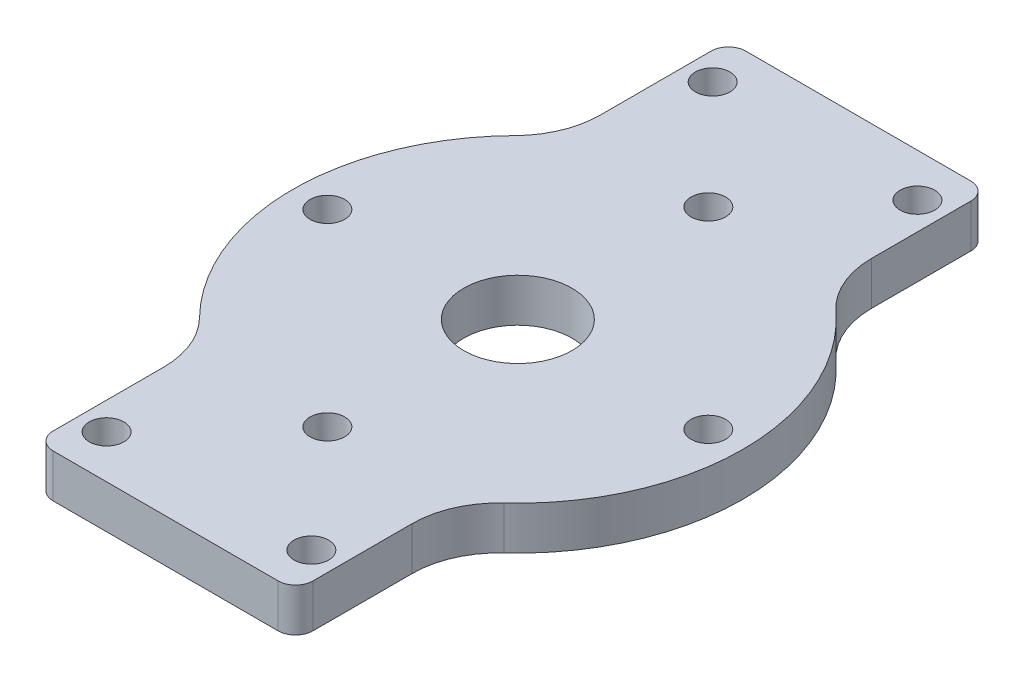
SolidWorks part; units mm, degrees
material "Hexcel AS4C (3000 Filaments)"
ref_plane "Ön Düzlem" through (0, 0, 0) normal (0, 0, 1) x (1, 0, 0)
ref_plane "Üst Düzlem" through (0, 0, 0) normal (0, 1, 0) x (1, 0, 0)
ref_plane "Sağ Düzlem" through (0, 0, 0) normal (1, 0, 0) x (0, 0, -1)
sketch "Çizim1" plane through (0, 0, 0) normal (0, 1, 0) x (1, 0, 0)
  line L0 (0, 40) -> (0, -40) construction
  line L1 (-15.6757, 40) -> (-15.6757, 25.2341)
  line L2 (14.3243, 40) -> (14.3243, 26.5392)
  line L3 (-15.6757, 40) -> (14.3243, 40)
  line L4 (-15.6757, -40) -> (14.3243, -40)
  line L5 (14.3243, -26.5392) -> (14.3243, -40)
  line L6 (14.3243, 40) -> (14.3243, -40) construction
  line L7 (-15.6757, -25.2341) -> (-15.6757, -40)
  line L8 (-15.6757, 40) -> (-15.6757, -40) construction
  arc A0 (-18.5435, 18.2246) -> (-18.5435, -18.2246) centre (0, 0) ccw
  arc A1 (17.5676, -19.1672) -> (17.5676, 19.1672) centre (0, 0) ccw
  arc A2 (-15.6757, -25.2341) -> (-18.5435, -18.2246) centre (-25.6757, -25.2341) ccw
  arc A3 (14.3243, -26.5392) -> (17.5676, -19.1672) centre (24.3243, -26.5392) cw
  arc A4 (14.3243, 26.5392) -> (17.5676, 19.1672) centre (24.3243, 26.5392) ccw
  arc A5 (-15.6757, 25.2341) -> (-18.5435, 18.2246) centre (-25.6757, 25.2341) cw
  point P6 (0, 0)
  point P17 (14.3243, -21.6982)
  dimension "D1" = 52
  dimension "D4" = 10
  dimension "D5" = 80
  dimension "D2" = 30
extrude "Yükseklik-Ekstrüzyon1" add sketch "Çizim1" along normal mid plane 5
sketch "Çizim2" plane through (0, 2.5, 0) normal (0, 1, 0) x (1, 0, 0)
  circle A0 centre (-22, 0) radius 2
  circle A1 centre (22, 0) radius 2
  dimension "D1" = 4
  dimension "D2" = 22
  dimension "D3" = 44
extrude "Kes-Ekstrüzyon1" cut sketch "Çizim2" against normal blind 27
pattern_circular "Dairesel Kaplama1" count 2 every 90 about axis through (-0.2467, 0, 0) along (0, 1, 0) of "Kes-Ekstrüzyon1"
sketch "Çizim3" plane through (0, 2.5, 0) normal (0, 1, 0) x (1, 0, 0)
  circle A0 centre (0, 0) radius 6.25
  dimension "D1" = 12.5
extrude "Kes-Ekstrüzyon2" cut sketch "Çizim3" against normal blind 27
sketch "Çizim4" plane through (0, 2.5, 0) normal (0, 1, 0) x (1, 0, 0)
  line L0 (-0.6757, 40) -> (-0.6757, 35) construction
  line L1 (-0.6757, 35) -> (11.1486, 35) construction
  line L2 (14.3243, 40) -> (-15.6757, 40) construction
  line L3 (-0.6757, 35) -> (-12.5, 35) construction
  circle A0 centre (-12.5, 35) radius 2
  circle A1 centre (11.1486, 35) radius 2
  dimension "D1" = 4
  dimension "D3" = 12.5
  dimension "D4" = 5
extrude "Kes-Ekstrüzyon3" cut sketch "Çizim4" against normal blind 27
mirror "Aynalama1" about plane through (0, 0, 0) normal (0, 0, 1) of "Kes-Ekstrüzyon3"
fillet "Radyus1" radius 2 4 edges at (14.3243, 0, -40) (14.3243, 0, 40) (-15.6757, 0, 40) (-15.6757, 0, -40)
